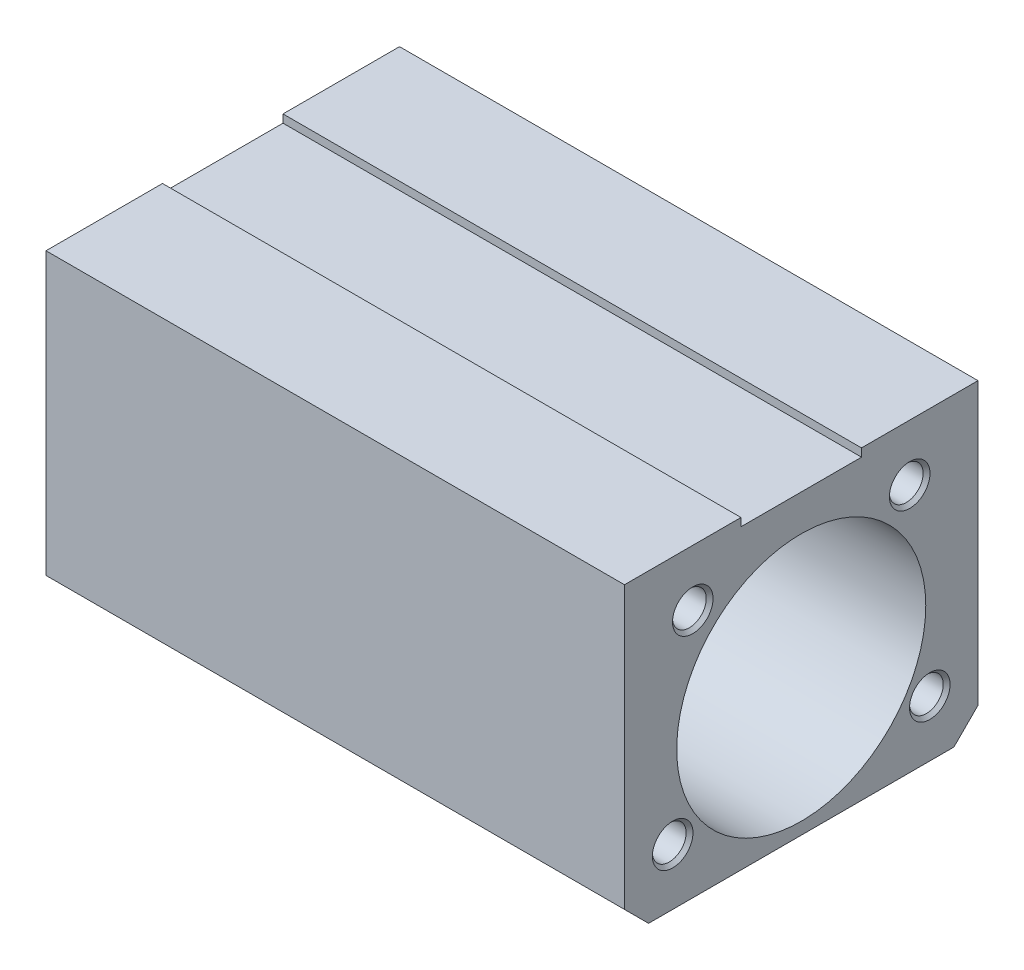
SolidWorks part; units mm, degrees
ref_plane "Plano frontal" through (0, 0, 0) normal (0, 0, 1) x (1, 0, 0)
ref_plane "Plano superior" through (0, 0, 0) normal (0, 1, 0) x (1, 0, 0)
ref_plane "Plano direito" through (0, 0, 0) normal (1, 0, 0) x (0, 0, -1)
sketch "Esboço1" plane through (0, 0, 0) normal (1, 0, 0) x (0, 0, -1)
  line L1 (0, 0) -> (44, 0)
  line L2 (0, 0) -> (0, 38)
  line L3 (0, 38) -> (44, 38)
  line L4 (44, 0) -> (44, 38)
  dimension "D1" = 44
  dimension "D2" = 38
extrude "Ressalto-extrusão1" add sketch "Esboço1" against normal blind 72
sketch "Esboço2" plane through (0, 0, 0) normal (1, 0, 0) x (0, 0, -1)
  line L0 (0, 0) -> (44, 0) construction
  line L1 (44, 0) -> (44, 38) construction
  circle A0 centre (22, 17) radius 15.5
  dimension "D1" = 31
  dimension "D2" = 1.5
  dimension "D3" = 22
extrude "Corte-extrusão1" cut sketch "Esboço2" against normal blind 66
sketch "Esboço4" plane through (-66, 0, 0) normal (1, 0, 0) x (0, 0, -1)
  circle A0 centre (22, 17) radius 9
  dimension "D1" = 18
extrude "Corte-extrusão2" cut sketch "Esboço4" against normal through all
hole_wizard "Furo roscado de M51" positions "Esboço5" profile "Esboço6" tap size "M5" standard "ISO"
sketch "Esboço5" plane through (0, 0, 0) normal (1, 0, 0) x (0, 0, -1)
  line L0 (44, 38) -> (0, 38) construction
  line L1 (0, 0) -> (44, 0) construction
  point P0 (8.5, 31)
  point P2 (35.5, 31)
  point P4 (38, 7)
  point P6 (6, 7)
  point P13 (22, 38)
  point P19 (22, 0)
  dimension "D1" = 27
  dimension "D2" = 7
  dimension "D3" = 13.5
  dimension "D4" = 32
  dimension "D5" = 7
  dimension "D6" = 16
sketch "Esboço6" plane through (0, 31, -8.5) normal (0, 1, 0) x (0, 0, -1)
  line L0 (0, 0) -> (0, 18)
  line L1 (0, 18) -> (2.1, 16.7382)
  line L2 (2.1, 16.7382) -> (2.1, 0.425)
  line L3 (2.1, 0.425) -> (2.525, 0)
  line L5 (2.525, 0) -> (0, 0)
  line L6 (-2.1, 0.425) -> (-2.525, 0) construction
  line L10 (0, 18) -> (-2.1, 16.7382) construction
  line L11 (0, -6.35) -> (0, 107.95) construction
  dimension "Tap Drill Dia." = 4.2
  dimension "Tap Drill Depth" = 18
  dimension "Near C'Sink Dia." = 5.05
  dimension "Near C'Sink Angle" = 90
  dimension "Drill Angle" = 118
chamfer "Chanfro1" distance 3 angle 45 2 edges at (-36, 0, -44) (-36, 0, 0)
sketch "Esboço7" plane through (0, 0, 0) normal (1, 0, 0) x (0, 0, -1)
  line L0 (44, 38) -> (0, 38) construction
  line L1 (14.5, 38) -> (29.5, 38)
  line L2 (14.5, 38) -> (14.5, 37)
  line L3 (14.5, 37) -> (29.5, 37)
  line L4 (29.5, 38) -> (29.5, 37)
  line L5 (0, 38) -> (0, 3) construction
  point P8 (22, 38)
  dimension "D1" = 1
  dimension "D2" = 15
  dimension "D3" = 22
extrude "Corte-extrusão3" cut sketch "Esboço7" against normal through all
